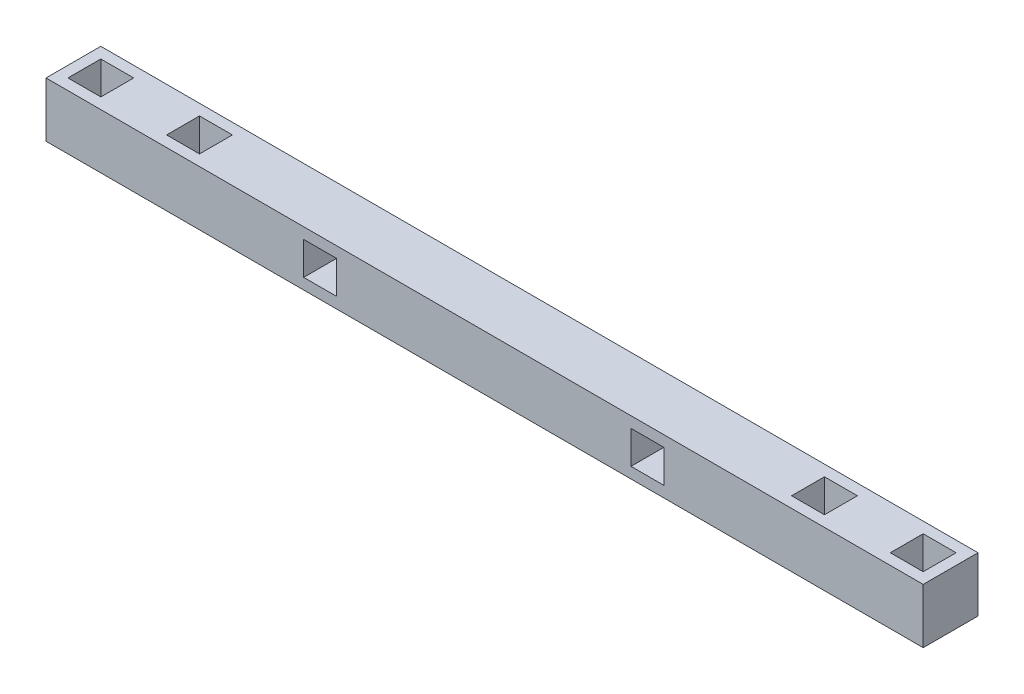
SolidWorks part; units mm, degrees
ref_plane "Front Plane" through (0, 0, 0) normal (0, 0, 1) x (1, 0, 0)
ref_plane "Top Plane" through (0, 0, 0) normal (0, 1, 0) x (1, 0, 0)
ref_plane "Right Plane" through (0, 0, 0) normal (1, 0, 0) x (0, 0, -1)
sketch "Sketch1" plane through (0, 0, 0) normal (0, 0, 1) x (1, 0, 0)
  line L1 (0, 0) -> (80, 0)
  line L2 (0, 0) -> (0, 5)
  line L3 (0, 5) -> (80, 5)
  line L4 (80, 0) -> (80, 5)
  line L5 (53.35, 4) -> (56.35, 4)
  line L6 (53.35, 4) -> (53.35, 1)
  line L7 (53.35, 1) -> (56.35, 1)
  line L8 (56.35, 4) -> (56.35, 1)
  line L9 (23.5, 4) -> (26.5, 4)
  line L10 (23.5, 4) -> (23.5, 1)
  line L11 (23.5, 1) -> (26.5, 1)
  line L12 (26.5, 4) -> (26.5, 1)
  dimension "D1" = 80
  dimension "D2" = 5
  dimension "D3" = 3
  dimension "D4" = 3
  dimension "D5" = 3
  dimension "D6" = 3
  dimension "D7" = 1
  dimension "D8" = 1
  dimension "D9" = 23.65
  dimension "D10" = 53.5
extrude "Boss-Extrude1" add sketch "Sketch1" along normal blind 5
sketch "Sketch2" plane through (0, 5, 0) normal (0, 1, 0) x (1, 0, 0)
  line L0 (80, 0) -> (0, 0) construction
  line L1 (76, -1) -> (79, -1)
  line L2 (76, -1) -> (76, -4)
  line L3 (76, -4) -> (79, -4)
  line L4 (79, -1) -> (79, -4)
  line L5 (1, -1) -> (4, -1)
  line L6 (1, -1) -> (1, -4)
  line L7 (1, -4) -> (4, -4)
  line L8 (4, -1) -> (4, -4)
  line L9 (80, -5) -> (80, 0) construction
  line L10 (0, -5) -> (0, 0) construction
  line L11 (80, -5) -> (0, -5) construction
  line L12 (10, -1) -> (13, -1)
  line L13 (10, -1) -> (10, -4)
  line L14 (10, -4) -> (13, -4)
  line L15 (13, -1) -> (13, -4)
  line L16 (67, -1) -> (70, -1)
  line L17 (67, -1) -> (67, -4)
  line L18 (67, -4) -> (70, -4)
  line L19 (70, -1) -> (70, -4)
  point P14 (0, -2.5)
  dimension "D1" = 3
  dimension "D2" = 3
  dimension "D3" = 1
  dimension "D4" = 1
  dimension "D5" = 1
  dimension "D6" = 1
  dimension "D7" = 3
  dimension "D8" = 3
  dimension "D9" = 3
  dimension "D10" = 3
  dimension "D11" = 1
  dimension "D12" = 6
  dimension "D13" = 3
  dimension "D14" = 3
  dimension "D15" = 1
  dimension "D16" = 6
extrude "Cut-Extrude1" cut sketch "Sketch2" against normal blind 5
